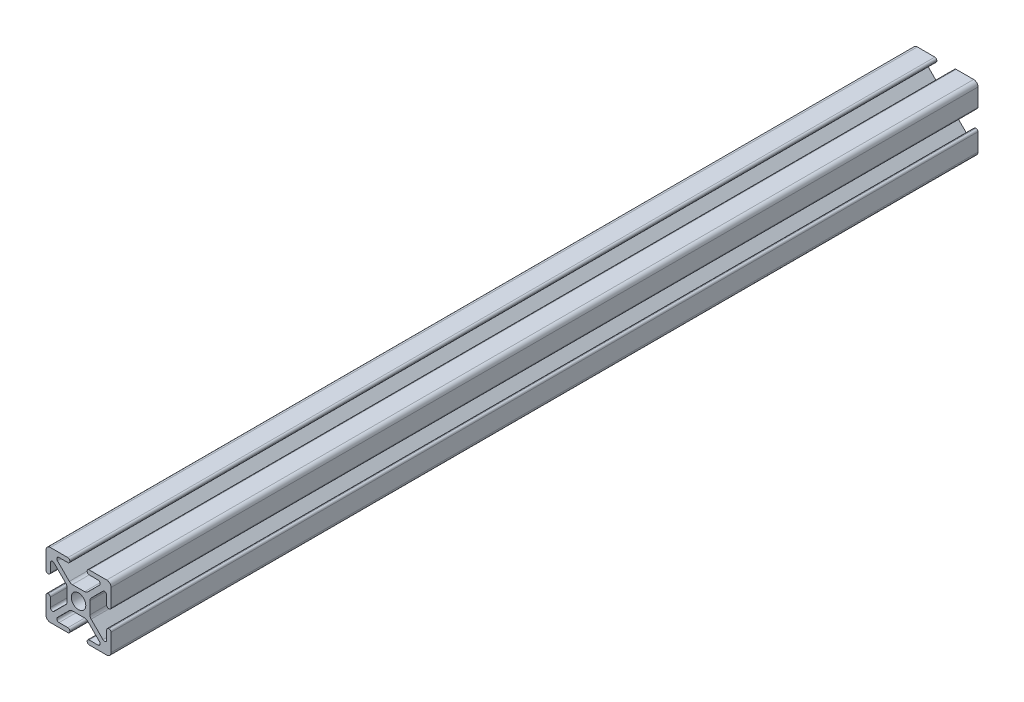
SolidWorks part; units mm, degrees
material "6061-T4 (SS)"
ref_plane "right plane" through (0, 0, 0) normal (0, 0, 1) x (1, 0, 0)
ref_plane "上视基准面" through (0, 0, 0) normal (0, 1, 0) x (1, 0, 0)
ref_plane "右视基准面" through (0, 0, 0) normal (1, 0, 0) x (0, 0, -1)
sketch "草图1" plane through (0, 0, 0) normal (0, 0, 1) x (1, 0, 0)
  line L0 (14.1, -4) -> (13.9, -4)
  line L1 (11.2929, -9.6929) -> (5.8358, -4.2358)
  line L2 (5.25, -2.8216) -> (5.25, 2.8216)
  line L3 (5.8358, 4.2358) -> (11.2929, 9.6929)
  line L4 (9.6929, 11.2929) -> (4.2358, 5.8358)
  line L5 (2.8216, 5.25) -> (-2.8216, 5.25)
  line L6 (-4.2358, 5.8358) -> (-9.6929, 11.2929)
  line L7 (-11.2929, 9.6929) -> (-5.8358, 4.2358)
  line L8 (-5.25, 2.8216) -> (-5.25, -2.8216)
  line L9 (-5.8358, -4.2358) -> (-11.2929, -9.6929)
  line L10 (-9.6929, -11.2929) -> (-4.2358, -5.8358)
  line L11 (-2.8216, -5.25) -> (2.8216, -5.25)
  line L12 (4.2358, -5.8358) -> (9.6929, -11.2929)
  line L13 (8.9858, -13) -> (4.9, -13)
  line L14 (4, -13.9) -> (4, -14.1)
  line L15 (15, -4.9) -> (15, -13)
  line L16 (4.9, -15) -> (13, -15)
  line L17 (13, -8.9858) -> (13, -4.9)
  line L18 (14.1, 4) -> (13.9, 4)
  line L19 (8.9858, 13) -> (4.9, 13)
  line L20 (4, 13.9) -> (4, 14.1)
  line L21 (4.9, 15) -> (13, 15)
  line L22 (15, 4.9) -> (15, 13)
  line L23 (13, 8.9858) -> (13, 4.9)
  line L24 (-14.1, -4) -> (-13.9, -4)
  line L25 (-8.9858, -13) -> (-4.9, -13)
  line L26 (-4, -13.9) -> (-4, -14.1)
  line L27 (-4.9, -15) -> (-13, -15)
  line L28 (-15, -4.9) -> (-15, -13)
  line L29 (-13, -8.9858) -> (-13, -4.9)
  line L30 (-14.1, 4) -> (-13.9, 4)
  line L31 (-8.9858, 13) -> (-4.9, 13)
  line L32 (-4, 13.9) -> (-4, 14.1)
  line L33 (-4.9, 15) -> (-13, 15)
  line L34 (-15, 4.9) -> (-15, 13)
  line L35 (-13, 8.9858) -> (-13, 4.9)
  circle A0 centre (0, 0) radius 3.35
  arc A1 (11.2929, -9.6929) -> (13, -8.9858) centre (12, -8.9858) ccw
  arc A2 (5.25, -2.8216) -> (5.8358, -4.2358) centre (7.25, -2.8216) ccw
  arc A3 (5.8358, 4.2358) -> (5.25, 2.8216) centre (7.25, 2.8216) ccw
  arc A4 (13, 8.9858) -> (11.2929, 9.6929) centre (12, 8.9858) ccw
  arc A5 (9.6929, 11.2929) -> (8.9858, 13) centre (8.9858, 12) ccw
  arc A6 (2.8216, 5.25) -> (4.2358, 5.8358) centre (2.8216, 7.25) ccw
  arc A7 (-4.2358, 5.8358) -> (-2.8216, 5.25) centre (-2.8216, 7.25) ccw
  arc A8 (-8.9858, 13) -> (-9.6929, 11.2929) centre (-8.9858, 12) ccw
  arc A9 (-11.2929, 9.6929) -> (-13, 8.9858) centre (-12, 8.9858) ccw
  arc A10 (-5.25, 2.8216) -> (-5.8358, 4.2358) centre (-7.25, 2.8216) ccw
  arc A11 (-5.8358, -4.2358) -> (-5.25, -2.8216) centre (-7.25, -2.8216) ccw
  arc A12 (-13, -8.9858) -> (-11.2929, -9.6929) centre (-12, -8.9858) ccw
  arc A13 (-9.6929, -11.2929) -> (-8.9858, -13) centre (-8.9858, -12) ccw
  arc A14 (-2.8216, -5.25) -> (-4.2358, -5.8358) centre (-2.8216, -7.25) ccw
  arc A15 (4.2358, -5.8358) -> (2.8216, -5.25) centre (2.8216, -7.25) ccw
  arc A16 (8.9858, -13) -> (9.6929, -11.2929) centre (8.9858, -12) ccw
  arc A17 (13.9, -4) -> (13, -4.9) centre (13.9, -4.9) ccw
  arc A18 (15, -4.9) -> (14.1, -4) centre (14.1, -4.9) ccw
  arc A19 (4.9, -13) -> (4, -13.9) centre (4.9, -13.9) ccw
  arc A20 (4, -14.1) -> (4.9, -15) centre (4.9, -14.1) ccw
  arc A21 (13, -15) -> (15, -13) centre (13, -13) ccw
  arc A22 (13, 4.9) -> (13.9, 4) centre (13.9, 4.9) ccw
  arc A23 (4, 13.9) -> (4.9, 13) centre (4.9, 13.9) ccw
  arc A24 (4.9, 15) -> (4, 14.1) centre (4.9, 14.1) ccw
  arc A25 (15, 13) -> (13, 15) centre (13, 13) ccw
  arc A26 (14.1, 4) -> (15, 4.9) centre (14.1, 4.9) ccw
  arc A27 (-13, -4.9) -> (-13.9, -4) centre (-13.9, -4.9) ccw
  arc A28 (-4, -13.9) -> (-4.9, -13) centre (-4.9, -13.9) ccw
  arc A29 (-4.9, -15) -> (-4, -14.1) centre (-4.9, -14.1) ccw
  arc A30 (-15, -13) -> (-13, -15) centre (-13, -13) ccw
  arc A31 (-14.1, -4) -> (-15, -4.9) centre (-14.1, -4.9) ccw
  arc A32 (-13.9, 4) -> (-13, 4.9) centre (-13.9, 4.9) ccw
  arc A33 (-4.9, 13) -> (-4, 13.9) centre (-4.9, 13.9) ccw
  arc A34 (-4, 14.1) -> (-4.9, 15) centre (-4.9, 14.1) ccw
  arc A35 (-13, 15) -> (-15, 13) centre (-13, 13) ccw
  arc A36 (-15, 4.9) -> (-14.1, 4) centre (-14.1, 4.9) ccw
  point P0 (0, 0.001)
  point P1 (0.001, 0.001)
  point P2 (0.001, 0)
extrude "凸台-拉伸1" add sketch "草图1" along normal blind 400
